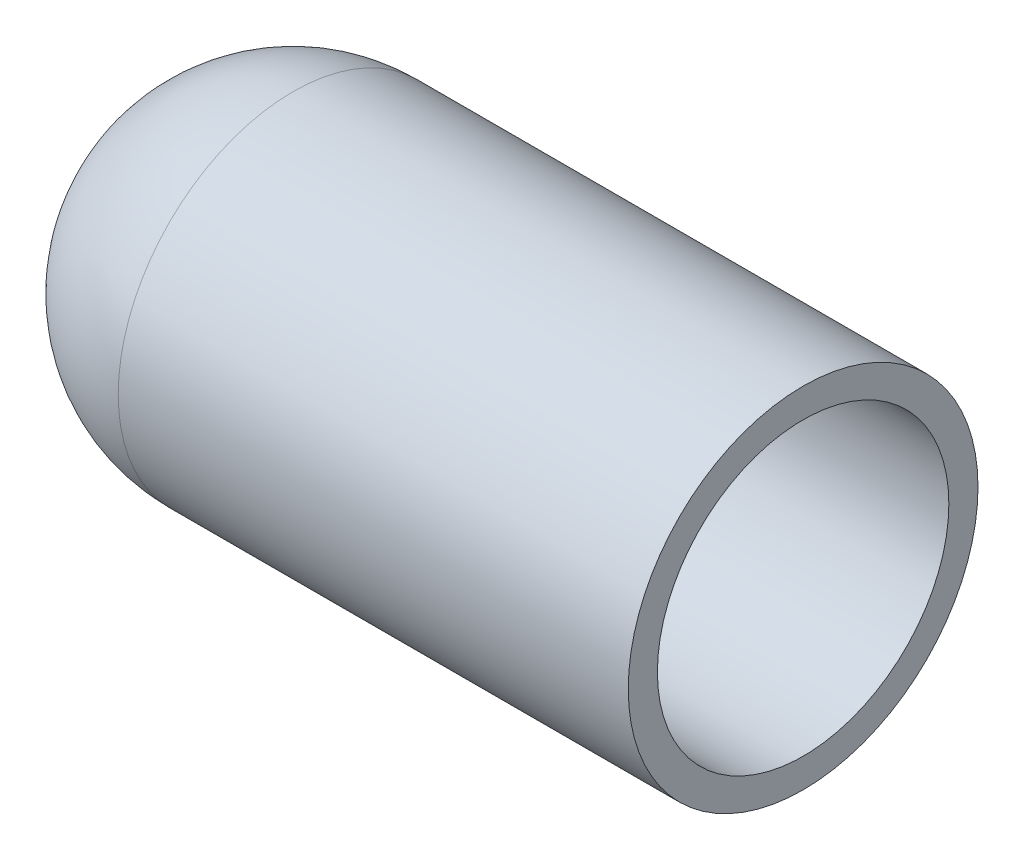
SolidWorks part; units mm, degrees
ref_plane "Front Plane" through (0, 0, 0) normal (0, 0, 1) x (1, 0, 0)
ref_plane "Top Plane" through (0, 0, 0) normal (0, 1, 0) x (1, 0, 0)
ref_plane "Right Plane" through (0, 0, 0) normal (1, 0, 0) x (0, 0, -1)
sketch "Sketch1" plane through (0, 0, 0) normal (0, 1, 0) x (1, 0, 0)
  line L0 (-16.16, 0) -> (18.84, 0) construction
  line L1 (-16.16, 12) -> (18.84, 12)
  line L3 (18.84, 12) -> (18.84, 0)
  line L4 (18.84, 0) -> (-28.16, 0)
  arc A0 (-16.16, 12) -> (-28.16, 0) centre (-16.16, 0) ccw
  point P3 (-0.535, 0)
  dimension "D2" = 12
  dimension "D1" = 35
revolve "Revolve1" add sketch "Sketch1" angle 360 about L0
shell "Shell1" thickness 2
